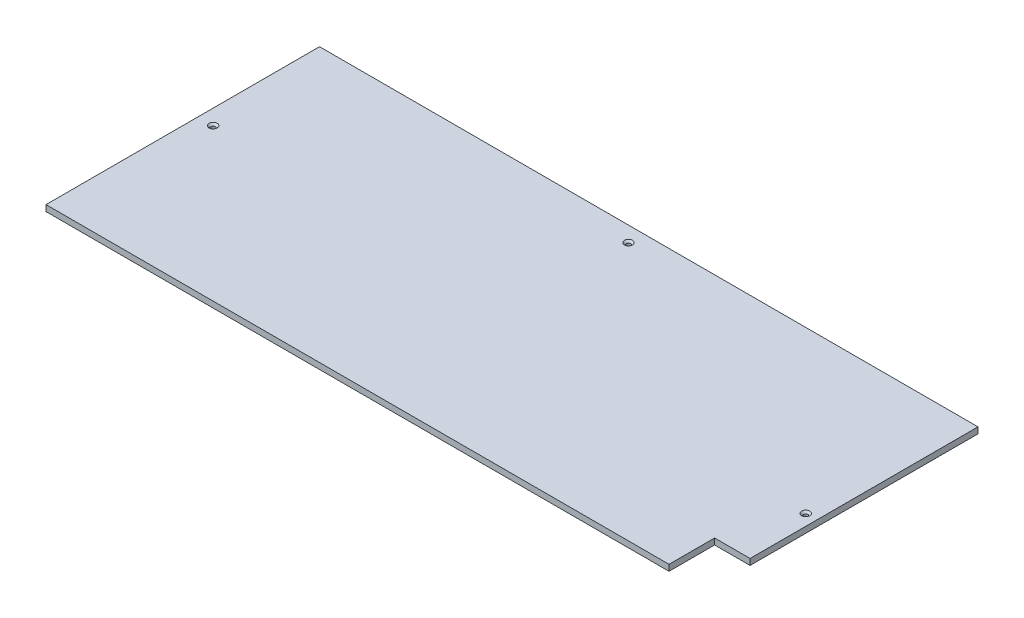
SolidWorks part; units mm, degrees
material "Balsa"
ref_plane "Front Plane" through (0, 0, 0) normal (0, 0, 1) x (1, 0, 0)
ref_plane "Top Plane" through (0, 0, 0) normal (0, 1, 0) x (1, 0, 0)
ref_plane "Right Plane" through (0, 0, 0) normal (1, 0, 0) x (0, 0, -1)
sketch "Sketch1" plane through (0, 0, 0) normal (0, 1, 0) x (1, 0, 0)
  line L1 (325, -150) -> (-325, -150)
  line L2 (325, -150) -> (325, 120)
  line L3 (325, 120) -> (-325, 120)
  line L4 (-325, -150) -> (-325, 120)
  point P0 (0, 0)
  dimension "D1" = 270
  dimension "D2" = 650
extrude "Boss-Extrude1" add sketch "Sketch1" along normal blind 6
sketch "Sketch2" plane through (0, 6, 0) normal (0, 1, 0) x (1, 0, 0)
  line L0 (-325, -150) -> (325, -150) construction
  line L1 (332.7558, 136.8148) -> (290, 136.8148)
  line L2 (332.7558, 136.8148) -> (332.7558, 40)
  line L3 (332.7558, 40) -> (290, 40)
  line L4 (290, 136.8148) -> (290, 40)
  line L5 (-337.1113, -127.8796) -> (-245, -127.8796)
  line L6 (-337.1113, -127.8796) -> (-337.1113, -140)
  line L7 (-337.1113, -140) -> (-245, -140)
  line L8 (-245, -127.8796) -> (-245, -140)
  line L9 (325, -150) -> (325, 120) construction
  line L10 (325, 120) -> (-325, 120) construction
  line L11 (-325, 120) -> (-325, -150) construction
  line L13 (337.9334, -185.1999) -> (290, -185.1999)
  line L14 (337.9334, -185.1999) -> (337.9334, -105)
  line L15 (337.9334, -105) -> (290, -105)
  line L16 (290, -185.1999) -> (290, -105)
  line M6 (-325, -150) -> (325, -150)
  line M7 (325, -150) -> (325, 120)
  dimension "D1" = 10
  dimension "D2" = 35
  dimension "D3" = 80
  dimension "D4" = 80
  dimension "D5" = 35
  dimension "D6" = 45
extrude "Cut-Extrude1" cut sketch "Sketch2" against normal through all contours L16 L15 M6 M7 | L16 L13 L14 L15 M7 M6
hole_wizard "CSK for M4 Flat Head Machine Screw1" positions "Sketch4" profile "Sketch5" countersink size "M4" standard "ANSI Metric" end condition through all
sketch "Sketch4" plane through (0, 6, 0) normal (0, 1, 0) x (1, 0, 0)
  line L0 (-325, 120) -> (-325, -150) construction
  line L1 (325, 120) -> (-325, 120) construction
  line L2 (325, -105) -> (325, 120) construction
  point P0 (-310, 0)
  point P2 (-5, 105)
  point P9 (314, -39)
  dimension "D1" = 15
  dimension "D2" = 15
  dimension "D3" = 120
  dimension "D4" = 320
  dimension "D5" = 159
  dimension "D6" = 11
sketch "Sketch5" plane through (-310, 6, 0) normal (1, 0, 0) x (0, 0, 1)
  line L0 (0, 0) -> (0, 6)
  line L1 (0, 6) -> (2.1, 6)
  line L2 (2.1, 6) -> (2.1, 1.9)
  line L3 (2.1, 1.9) -> (4, 0)
  line L5 (4, 0) -> (0, 0)
  line L6 (-2.1, 1.9) -> (-4, 0) construction
  line L11 (0, -6.35) -> (0, 107.95) construction
  dimension "Thru Hole Dia." = 4.2
  dimension "Thru Hole Depth" = 6
  dimension "Near C'Sink Dia." = 8
  dimension "Near C'Sink Angle" = 90
